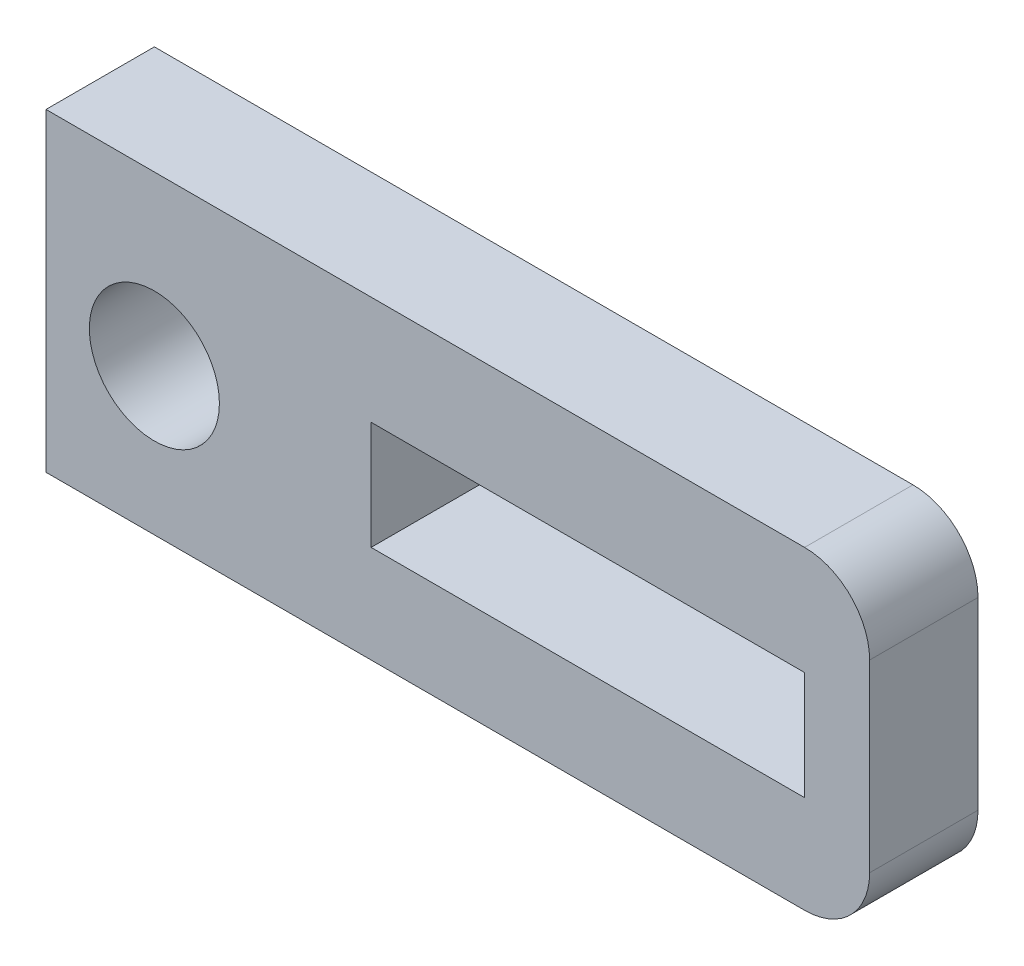
SolidWorks part; units mm, degrees
ref_plane "Front Plane" through (0, 0, 0) normal (0, 0, 1) x (1, 0, 0)
ref_plane "Top Plane" through (0, 0, 0) normal (0, 1, 0) x (1, 0, 0)
ref_plane "Right Plane" through (0, 0, 0) normal (1, 0, 0) x (0, 0, -1)
sketch "Sketch1" plane through (0, 0, 0) normal (0, 0, 1) x (1, 0, 0)
  line L0 (7, 6.5) -> (7, 8)
  line L2 (0, 6.5) -> (0, 8)
  line L3 (7, 15) -> (77, 15)
  line L4 (80, 2.9617) -> (80, 12)
  line L5 (7, 7.25) -> (47, 7.25)
  line L6 (42, 15) -> (42, 0.5)
  line L18 (77, 10) -> (57, 10)
  line L19 (77, 10) -> (77, 5)
  line L20 (77, 5) -> (57, 5)
  line L21 (57, 10) -> (57, 5)
  line L22 (42, 0.5) -> (77, 0.5)
  line L23 (80, 3.5) -> (80, 21.1809)
  arc A0 (0, 8) -> (7, 15) centre (7, 8) cw
  arc A1 (7, -0.5) -> (0, 6.5) centre (7, 6.5) cw
  circle A2 centre (7, 7.25) radius 3
  circle A3 centre (47, 7.25) radius 3
  arc A4 (80, 12) -> (77, 15) centre (77, 12) ccw
  arc A11 (80, 3.5) -> (77, 0.5) centre (77, 3.5) cw
  point P7 (0, 15)
  point P17 (80, 15)
  dimension "D3" = 7
  dimension "D4" = 6
  dimension "D6" = 6
  dimension "D7" = 3
  dimension "D21" = 3
  dimension "D8" = 5
  dimension "D1" = 80
  dimension "D5" = 40
  dimension "D9" = 14.5
  dimension "D17" = 5
  dimension "D18" = 20
extrude "Boss-Extrude1" add sketch "Sketch1" along normal blind 5
